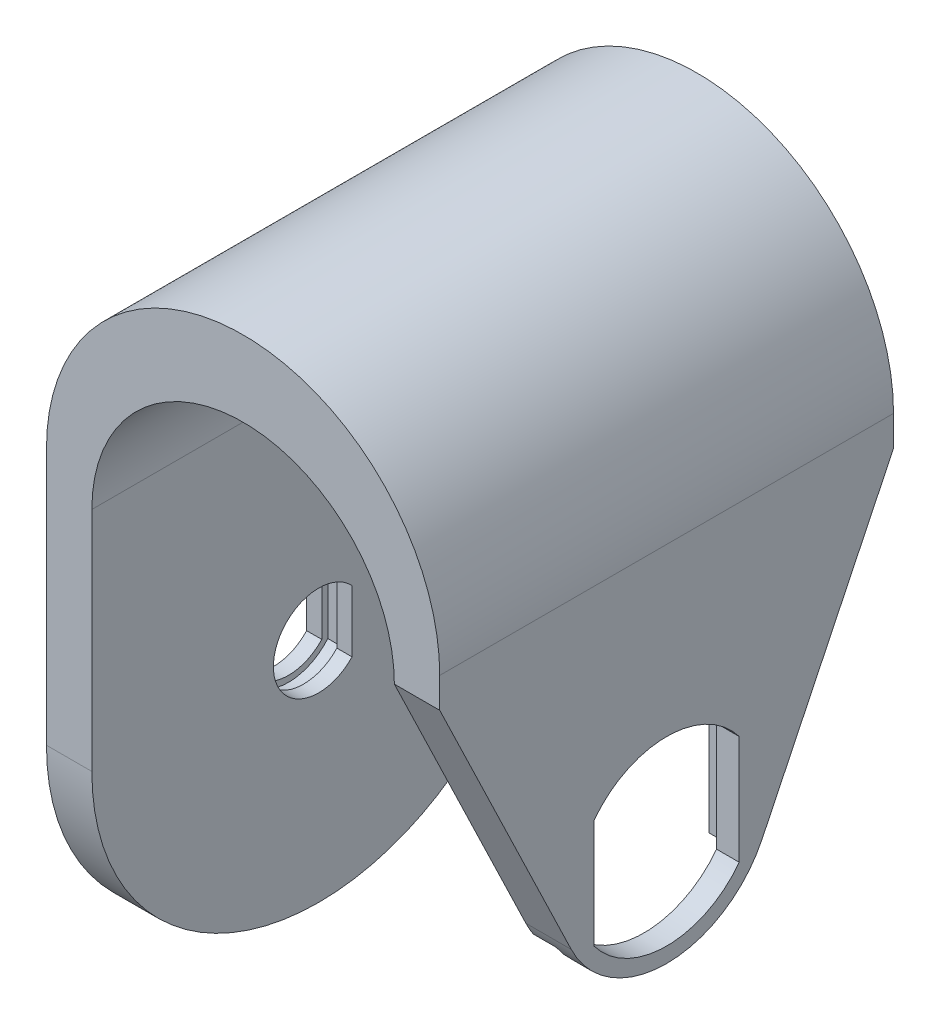
SolidWorks part; units mm, degrees
ref_plane "Front Plane" through (0, 0, 0) normal (0, 0, 1) x (1, 0, 0)
ref_plane "Top Plane" through (0, 0, 0) normal (0, 1, 0) x (1, 0, 0)
ref_plane "Right Plane" through (0, 0, 0) normal (1, 0, 0) x (0, 0, -1)
sketch "Sketch3" plane through (0, 0, 0) normal (0, 0, 1) x (1, 0, 0)
  line L2 (-25, 25) -> (-25, -50)
  line L5 (25, 25) -> (25, -50)
  line L9 (32.5, -50) -> (32.5, 30)
  line L10 (-32.5, -50) -> (-32.5, 30)
  line L11 (-32.5, -50) -> (-25, -50)
  line L12 (25, -50) -> (32.5, -50)
  arc A0 (-25, 25) -> (25, 25) centre (0, 25) cw
  arc A4 (-32.5, 30) -> (32.5, 30) centre (0, 30) cw
extrude "Extrude_Body" add sketch "Sketch3" along normal mid plane 75 contours A4 L9 L12 L5 A0 L2 L11 L10
sketch "Sketch4" plane through (25, 0, 0) normal (-1, 0, 0) x (0, 0, 1)
  line L2 (37.5, 25) -> (37.5, -50) construction
  line L4 (-37.5, 25) -> (-37.5, -50) construction
  line L11 (37.5, 25) -> (42.5, 25)
  line L12 (42.5, 25) -> (42.5, -55.0005)
  line L13 (-37.4993, 24.9995) -> (-42.4993, 24.9995)
  line L14 (-42.4993, 24.9995) -> (-42.4993, -55.0005)
  line L15 (-42.4993, -55.0005) -> (42.5, -55.0005)
  line L19 (37.5, 25) -> (15.7651, -20.0984)
  line L21 (-37.4993, 24.9995) -> (-15.7642, -20.0985)
  arc A3 (-15.7642, -20.0985) -> (15.7651, -20.0984) centre (0.0005, -12.5007) ccw
  point P5 (37.5, 17.5)
  point P20 (-37.5, 17.5)
extrude "ExtrCut_Bevels" cut sketch "Sketch4" against normal through all contours L12 L15 L14 L13 L21 A3 L19 L11
sketch "Sketch8" plane through (-25, 0, 0) normal (1, 0, 0) x (0, 0, -1)
  line L0 (-37.5, 25) -> (37.5, -50) construction
  line L1 (37.5, 25) -> (-37.5, -50) construction
  line L2 (37.5, 25) -> (37.5, -50) construction
  line L3 (-37.5, 25) -> (-37.5, -50) construction
  line L4 (-37.5, -12.5) -> (-42.5, -12.5)
  line L5 (37.5, -12.5) -> (42.5, -12.5)
  line L6 (42.5, -12.5) -> (42.5, -53.6278)
  line L7 (42.5, -53.6278) -> (-42.5, -53.6278)
  line L8 (-42.5, -53.6278) -> (-42.5, -12.5)
  arc A1 (37.5, -12.5) -> (-37.5, -12.5) centre (0, -12.5) cw
extrude "ExtrCut_RoundBevel" cut sketch "Sketch8" against normal through all
sketch "Sketch34" plane through (25, 0, 0) normal (-1, 0, 0) x (0, 0, 1)
  line L0 (0.0005, -12.5007) -> (-14.4995, -12.5007) construction
  line L1 (0.0005, -12.5007) -> (14.5005, -12.5007) construction
  line L2 (-14.4995, -2.7027) -> (-14.4995, -22.2986)
  line L3 (14.5005, -2.7027) -> (14.5005, -22.2986)
  arc A1 (14.5005, -2.7027) -> (-14.4995, -2.7027) centre (0.0005, -12.5007) ccw
  arc A2 (-14.4995, -22.2986) -> (14.5005, -22.2986) centre (0.0005, -12.5007) ccw
sketch "Sketch35" plane through (25, 0, 0) normal (-1, 0, 0) x (0, 0, 1)
  line L2 (0.0005, -12.5007) -> (-11.9995, -12.5007) construction
  line L3 (-11.9995, -3.5007) -> (-11.9995, -21.5007)
  line L4 (0.0005, -12.5007) -> (12.0005, -12.5007) construction
  line L5 (12.0005, -3.5007) -> (12.0005, -21.5007)
  arc A5 (12.0005, -3.5007) -> (-11.9995, -3.5007) centre (0.0005, -12.5007) ccw
  arc A6 (-11.9995, -21.5007) -> (12.0005, -21.5007) centre (0.0005, -12.5007) ccw
extrude "Cut-Extrude13" cut sketch "Sketch34" against normal mid plane 7.5
extrude "Cut-Extrude14" cut sketch "Sketch35" against normal up to next contours A5 L3 A6 L5
sketch "Sketch36" plane through (-32.5, 0, 0) normal (-1, 0, 0) x (0, 0, 1)
  line L0 (0, -12.5) -> (-5.5, -12.5) construction
  line L1 (-5.5, -7.401) -> (-5.5, -17.599)
  arc A1 (-5.5, -7.401) -> (-5.5, -17.599) centre (0, -12.5) cw
extrude "Cut-Extrude15" cut sketch "Sketch36" against normal up to next
ref_plane "Snap-in Plane" through (-28.75, 0, 0) normal (1, 0, 0) x (0, 0, -1)
sketch "Sketch37" plane through (-28.75, 0, 0) normal (1, 0, 0) x (0, 0, -1)
  line L0 (0, -12.5) -> (-8.5, -12.5) construction
  line L3 (6.5, -7.0228) -> (6.5, -17.9772)
  line L4 (0, -12.5) -> (5.5, -12.5) construction
  line L5 (5.5, -7.401) -> (5.5, -17.599) construction
  line L6 (5.5, -12.5) -> (6.5, -12.5) construction
  arc A1 (6.5, -7.0228) -> (6.5, -17.9772) centre (0, -12.5) ccw
extrude "Cut-Extrude16" cut sketch "Sketch37" against normal mid plane 2.5
